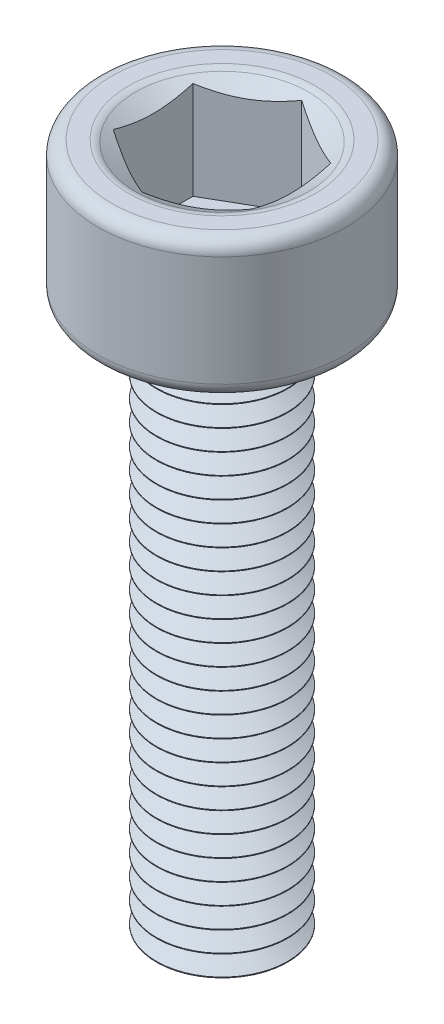
SolidWorks part; units mm, degrees
material "Plain Carbon Steel"
ref_plane "Front Plane" through (0, 0, 0) normal (0, 0, 1) x (1, 0, 0)
ref_plane "Top Plane" through (0, 0, 0) normal (0, 1, 0) x (1, 0, 0)
ref_plane "Right Plane" through (0, 0, 0) normal (1, 0, 0) x (0, 0, -1)
sketch "Sketch1" plane through (0, 0, 0) normal (0, 0, 1) x (1, 0, 0)
  line L0 (0, 2) -> (0, -8)
  line L1 (0, 2) -> (1.6, 2)
  line L2 (0, -8) -> (0.95, -8)
  line L3 (0.95, -8) -> (0.95, 0)
  line L4 (0.95, 0) -> (0, 0) construction
  line L5 (1.8, 1.8) -> (1.8, 0.2)
  line L6 (1.6, 0) -> (0.95, 0)
  arc A0 (1.6, 2) -> (1.8, 1.8) centre (1.6, 1.8) cw
  arc A1 (1.8, 0.2) -> (1.6, 0) centre (1.6, 0.2) cw
  dimension "D5" = 0.2
  dimension "D1" = 10
  dimension "D2" = 2
  dimension "D3" = 0.95
  dimension "D4" = 1.8
revolve "Revolve1" add sketch "Sketch1" angle 360 about L0
sketch "Sketch2" plane through (0, 2, 0) normal (0, 1, 0) x (1, 0, 0)
  line L1 (1, 0.5774) -> (0, 1.1547)
  line L2 (0, 1.1547) -> (-1, 0.5774)
  line L3 (-1, 0.5774) -> (-1, -0.5774)
  line L4 (-1, -0.5774) -> (0, -1.1547)
  line L5 (0, -1.1547) -> (1, -0.5774)
  line L6 (1, -0.5774) -> (1, 0.5774)
  circle A0 centre (0, 0) radius 1 construction
  dimension "D1" = 2
extrude "Cut-Extrude1" cut sketch "Sketch2" against normal blind 1.5
sketch "Sketch3" plane through (0, 2, 0) normal (0, 1, 0) x (1, 0, 0)
  circle A0 centre (0, 0) radius 1.3
  dimension "D1" = 2.6
extrude "Cut-Extrude2" cut sketch "Sketch3" against normal blind 1 draft 60
fillet "Fillet1" radius 0.2 1 edges at (-1.3, 2, 0)
sketch "Sketch4" plane through (0, 0, 0) normal (0, 0, 1) x (1, 0, 0)
  line L0 (0, 0) -> (0, -8) construction
  line L1 (-0.95, -8) -> (0.95, -8) construction
  line L2 (0, -8) -> (0.7, -8) construction
  line L3 (0.7, -8) -> (0.9598, -8) construction
  line L4 (0.9598, -8) -> (1.2598, -8) construction
  line L5 (1.2598, -7.85) -> (1.2598, -8.15)
  line L6 (0.9598, -7.85) -> (0.9598, -8.15) construction
  line L7 (1.2598, -7.85) -> (0.9598, -7.85)
  line L8 (0.9598, -7.85) -> (0.7, -8)
  line L9 (0.7, -8) -> (0.9598, -8.15)
  line L10 (0.9598, -8.15) -> (1.2598, -8.15)
  dimension "D1" = 0.3
  dimension "D2" = 60
  dimension "D3" = 0.7
revolve "Cut-Revolve1" cut sketch "Sketch4" angle 360 about L0
pattern_linear "LPattern1" count 26 spacing 0.3 along (0, 1, 0) of "Cut-Revolve1"
